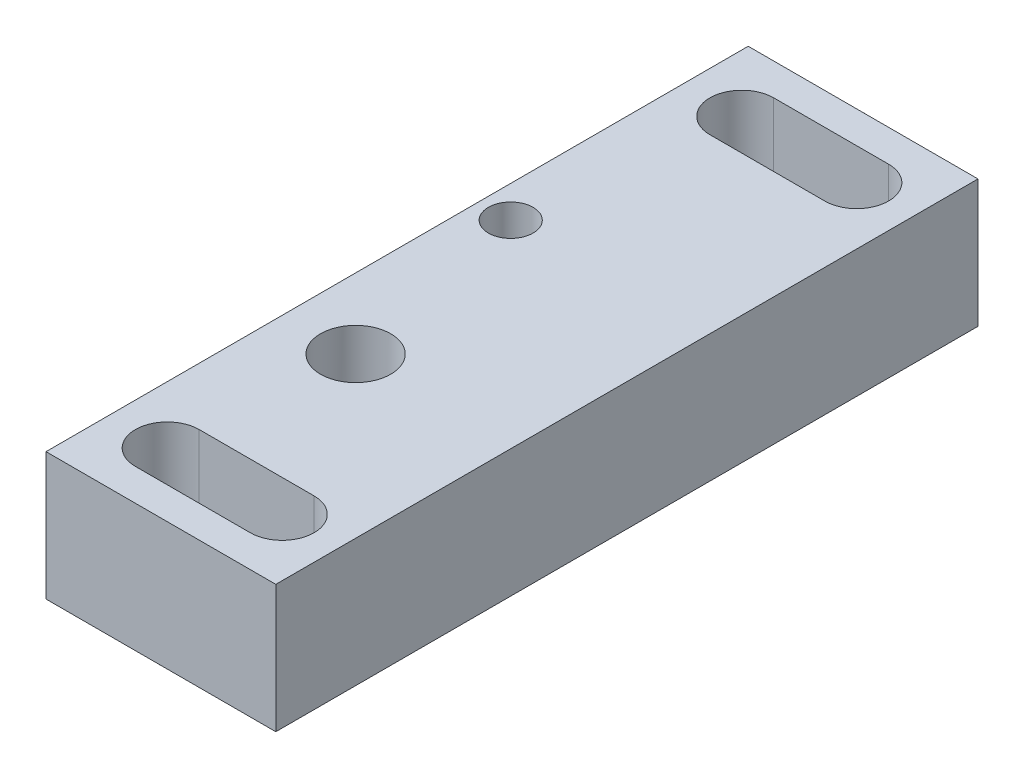
SolidWorks part; units mm, degrees
ref_plane "Front Plane" through (0, 0, 0) normal (0, 0, 1) x (1, 0, 0)
ref_plane "Top Plane" through (0, 0, 0) normal (0, 1, 0) x (1, 0, 0)
ref_plane "Right Plane" through (0, 0, 0) normal (1, 0, 0) x (0, 0, -1)
sketch "Sketch1" plane through (0, 0, 0) normal (0, 1, 0) x (1, 0, 0)
  line L1 (-9, 27.5) -> (9, 27.5)
  line L2 (-9, 27.5) -> (-9, -27.5)
  line L3 (-9, -27.5) -> (9, -27.5)
  line L4 (9, 27.5) -> (9, -27.5)
  line L5 (-9, 27.5) -> (9, -27.5) construction
  line L6 (-9, -27.5) -> (9, 27.5) construction
  point P0 (0, 0)
  dimension "D1" = 18
  dimension "D2" = 55
extrude "Boss-Extrude1" add sketch "Sketch1" along normal blind 10
sketch "Sketch2" plane through (0, 10, 0) normal (0, 1, 0) x (1, 0, 0)
  line L0 (3.5, -8.75) -> (3.5, -11.5) construction
  line L1 (3.5, -11.5) -> (3.5, -27.5) construction
  line L2 (-9, -27.5) -> (9, -27.5) construction
  line L3 (3.5, -8.75) -> (6.25, -8.75) construction
  line L4 (6.25, -8.75) -> (9, -8.75) construction
  line L5 (9, -27.5) -> (9, 27.5) construction
  line L6 (6.5, 6.4) -> (6.5, 8.15) construction
  line L7 (6.5, 8.15) -> (6.5, 27.5) construction
  line L8 (9, 27.5) -> (-9, 27.5) construction
  line L9 (6.5, 6.4) -> (8.25, 6.4) construction
  line L10 (8.25, 6.4) -> (9, 6.4) construction
  circle A0 centre (3.5, -8.75) radius 2.75
  circle A1 centre (6.5, 6.4) radius 1.75
  dimension "D1" = 3.5
  dimension "D2" = 5.5
  dimension "D3" = 2.75
  dimension "D4" = 16
  dimension "D5" = 0.75
  dimension "D6" = 19.35
extrude "Cut-Extrude1" cut sketch "Sketch2" against normal through all
sketch "Sketch3" plane through (0, 0, 0) normal (0, -1, 0) x (1, 0, 0)
  circle A0 centre (3.5, 8.75) radius 4.75
  dimension "D1" = 9.5
extrude "Cut-Extrude2" cut sketch "Sketch3" against normal blind 5.5
sketch "Sketch4" plane through (0, 0, 0) normal (0, -1, 0) x (1, 0, 0)
  line L0 (6.5, -9.4) -> (9, -9.4)
  line L1 (9, 27.5) -> (9, -27.5) construction
  line L2 (9, -9.4) -> (9, -3.4)
  line L3 (9, -3.4) -> (6.5, -3.4)
  circle A0 centre (6.5, -6.4) radius 3
  circle M2 centre (6.5, -6.4) radius 1.75
  line M3 (9, -27.5) -> (9, 27.5)
  dimension "D1" = 6
extrude "Cut-Extrude3" cut sketch "Sketch4" against normal blind 4 contours A0 L2 M2 | A0 L0 M3 | A0 L3 M3
sketch "Sketch5" plane through (0, 0, 0) normal (0, 1, 0) x (1, 0, 0)
  line L0 (-7, 22.5) -> (-4.5, 22.5) construction
  line L1 (-4.5, 22.5) -> (4.5, 22.5) construction
  line L2 (4.5, 22.5) -> (7, 22.5) construction
  line L3 (-4.5, 25) -> (4.5, 25)
  line L4 (4.5, 20) -> (-4.5, 20)
  line L5 (0, -22.5) -> (0, 22.5) construction
  line L6 (-9, 0) -> (9, 0) construction
  line L7 (-9, 27.5) -> (-9, -27.5) construction
  line L8 (9, -27.5) -> (9, 27.5) construction
  line L9 (9, 27.5) -> (-9, 27.5) construction
  line L10 (4.5, -22.5) -> (7, -22.5) construction
  line L11 (-4.5, -22.5) -> (4.5, -22.5) construction
  line L12 (-7, -22.5) -> (-4.5, -22.5) construction
  line L13 (4.5, -20) -> (-4.5, -20)
  line L14 (-4.5, -25) -> (4.5, -25)
  circle A0 centre (-4.5, 22.5) radius 2.5
  circle A1 centre (4.5, 22.5) radius 2.5
  circle A2 centre (4.5, -22.5) radius 2.5
  circle A3 centre (-4.5, -22.5) radius 2.5
  point P23 (0, 0)
  dimension "D1" = 5
  dimension "D2" = 14
  dimension "D3" = 2.5
extrude "Cut-Extrude4" cut sketch "Sketch5" along normal through all contours A0 | A1 L3 A0 L4 | A1 | A3 | L13 A3 L14 A2 | A2
mirror "Mirror2" about plane through (0, 0, 0) normal (1, 0, 0) of bodies 105
delete or keep bodies "Body-Delete/Keep 1" type delete bodies bodies 105
